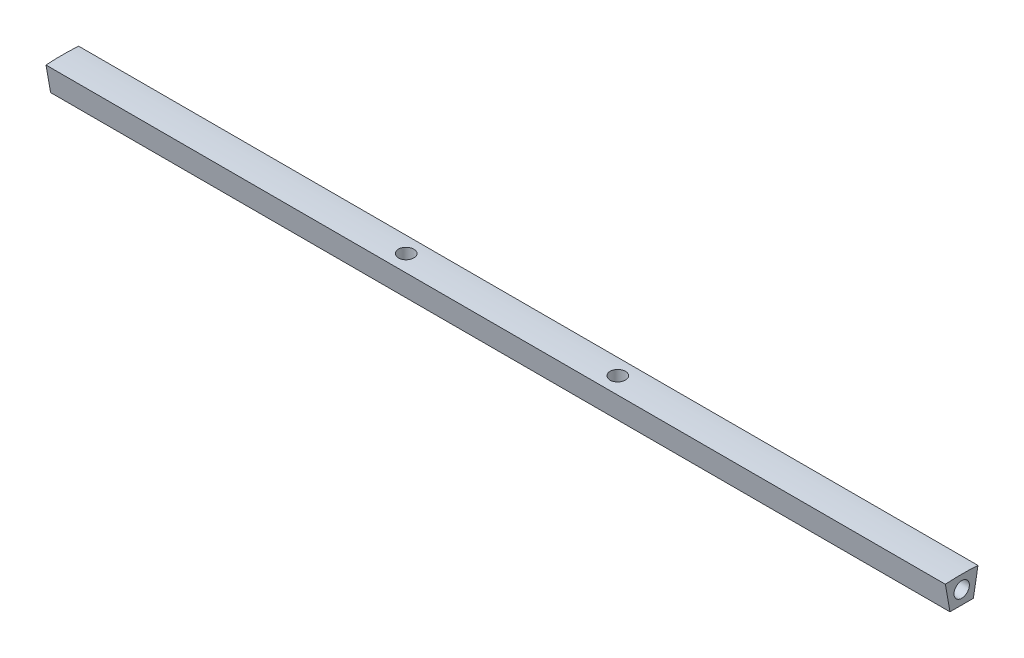
SolidWorks part; units mm, degrees
ref_plane "Спереди" through (0, 0, 0) normal (0, 0, 1) x (1, 0, 0)
ref_plane "Сверху" through (0, 0, 0) normal (0, 1, 0) x (1, 0, 0)
ref_plane "Справа" through (0, 0, 0) normal (1, 0, 0) x (0, 0, -1)
sketch "Эскиз1" plane through (0, 0, 0) normal (1, 0, 0) x (0, 0, -1)
  line L0 (-3.0855, 17.4987) -> (-2.2117, 12.5434)
  line L1 (0, -1000) -> (0, 49000) construction
  line L2 (2.2117, 12.5434) -> (3.0855, 17.4987)
  line L3 (-2.2117, 12.5434) -> (2.2117, 12.5434)
  arc A0 (-35.7, 0) -> (35.7, 0) centre (0, -27.3954) cw construction
  arc A1 (-29.146, 0) -> (29.146, 0) centre (0, -27.3954) cw construction
  arc A2 (-3.0855, 17.4987) -> (3.0855, 17.4987) centre (0, -27.3954) cw
  dimension "D1" = 45
  dimension "D2" = 5
  dimension "D3" = 71.4
  dimension "D4" = 10
extrude "Бобышка-Вытянуть1" add sketch "Эскиз1" along normal mid plane 170
sketch "Эскиз2" plane through (85, 0, 0) normal (1, 0, 0) x (0, 0, -1)
  circle A0 centre (0, 15.1046) radius 1.45
  arc A1 (3.0855, 17.4987) -> (-3.0855, 17.4987) centre (0, -27.3954) ccw construction
  arc A2 (3.0855, 17.4987) -> (-3.0855, 17.4987) centre (0, -27.3954) ccw construction
  circle A3 centre (0, -27.3954) radius 42.5 construction
  point P6 (0, 20.4901)
  dimension "D1" = 85
  dimension "D2" = 2.9
extrude "Вырез-Вытянуть1" cut sketch "Эскиз2" against normal blind 10
mirror "Зеркальное отражение1" about plane through (0, 0, 0) normal (1, 0, 0) of "Вырез-Вытянуть1"
sketch "Эскиз3" plane through (0, 12.5434, 0) normal (0, -1, 0) x (1, 0, 0)
  line L0 (0, -1000) -> (0, 49000) construction
  line L1 (-1000, 0) -> (49000, 0) construction
  circle A0 centre (-20, 0) radius 1.45
  circle A1 centre (20, 0) radius 1.45
  dimension "D2" = 2.9
  dimension "D1" = 20
extrude "Вырез-Вытянуть2" cut sketch "Эскиз3" against normal blind 10
